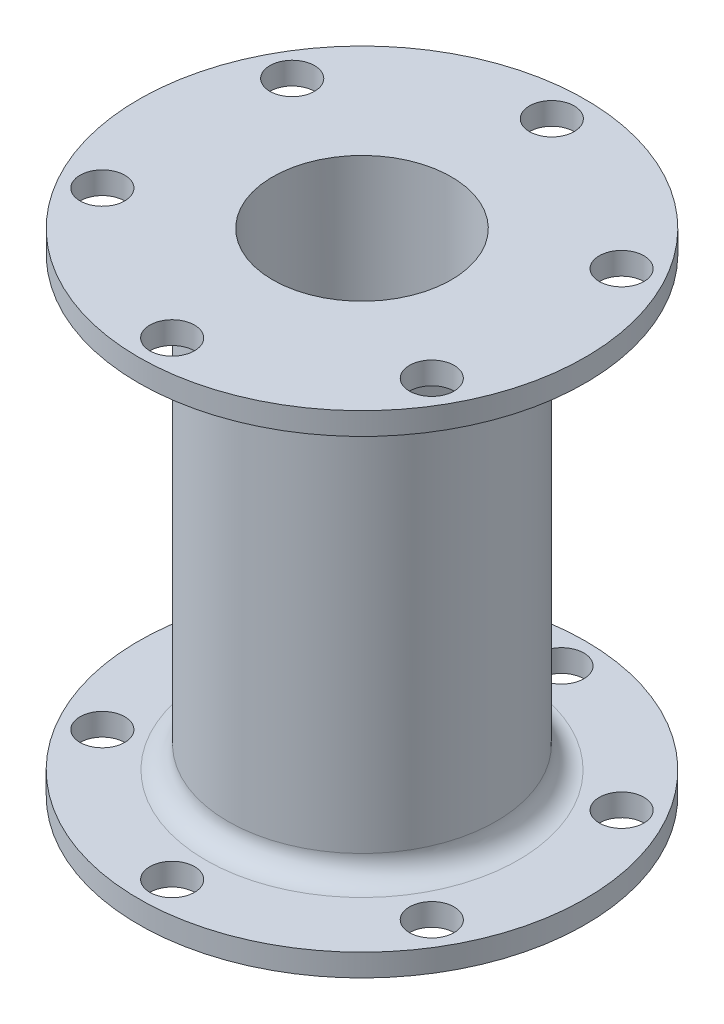
SolidWorks part; units mm, degrees
ref_plane "Front Plane" through (0, 0, 0) normal (0, 0, 1) x (1, 0, 0)
ref_plane "Top Plane" through (0, 0, 0) normal (0, 1, 0) x (1, 0, 0)
ref_plane "Right Plane" through (0, 0, 0) normal (1, 0, 0) x (0, 0, -1)
sketch "Sketch1" plane through (0, 0, 0) normal (0, 1, 0) x (1, 0, 0)
  circle A0 centre (0, 0) radius 127
extrude "Boss-Extrude1" add sketch "Sketch1" along normal blind 12.7
sketch "Sketch2" plane through (0, 12.7, 0) normal (0, 1, 0) x (1, 0, 0)
  circle A0 centre (0, 107.95) radius 12.7
  circle A1 centre (0, -107.95) radius 12.7
  circle A2 centre (-93.6625, 53.975) radius 12.7
  circle A3 centre (93.6625, 53.975) radius 12.7
  circle A4 centre (-93.6625, -53.975) radius 12.7
  circle A5 centre (93.6625, -53.975) radius 12.7
  dimension "D1" = 107.95
  dimension "D2" = 107.95
  dimension "D3" = 93.6625
  dimension "D4" = 53.975
  dimension "D5" = 53.975
  dimension "D6" = 53.975
  dimension "D7" = 53.975
  dimension "D8" = 93.6625
  dimension "D9" = 93.6625
  dimension "D10" = 93.6625
extrude "Cut-Extrude1" cut sketch "Sketch2" against normal blind 12.7
sketch "Sketch3" plane through (0, 0, 0) normal (0, -1, 0) x (1, 0, 0)
  circle A0 centre (0, 0) radius 76.2
extrude "Boss-Extrude2" add sketch "Sketch3" along normal blind 254
sketch "Sketch4" plane through (0, -254, 0) normal (0, -1, 0) x (1, 0, 0)
  circle A0 centre (0, 0) radius 127
extrude "Boss-Extrude3" add sketch "Sketch4" along normal blind 12.7
sketch "Sketch5" plane through (0, -266.7, 0) normal (0, -1, 0) x (1, 0, 0)
  circle A0 centre (0, 107.95) radius 12.7
  circle A1 centre (5.5103, -107.95) radius 12.7
  circle A2 centre (-93.6625, 53.975) radius 12.7
  circle A3 centre (93.6625, 53.975) radius 12.7
  circle A4 centre (-93.6625, -53.975) radius 12.7
  circle A5 centre (93.6625, -53.975) radius 12.7
  point P15 (-11.1778, 33.5333)
  point P16 (0, 0)
  dimension "D1" = 25.4
  dimension "D2" = 107.95
  dimension "D3" = 107.95
  dimension "D4" = 93.6625
  dimension "D5" = 53.975
  dimension "D6" = 53.975
  dimension "D7" = 93.6625
  dimension "D8" = 53.975
  dimension "D9" = 53.975
  dimension "D10" = 93.6625
  dimension "D11" = 93.6625
extrude "Cut-Extrude2" cut sketch "Sketch5" against normal blind 12.7
fillet "Fillet1" radius 12.7 2 edges at (0, -254, -76.2) (0, 0, 76.2)
sketch "Sketch6" plane through (0, 12.7, 0) normal (0, 1, 0) x (1, 0, 0)
  circle A0 centre (0, 0) radius 50.8
extrude "Cut-Extrude3" cut sketch "Sketch6" against normal blind 325.12
